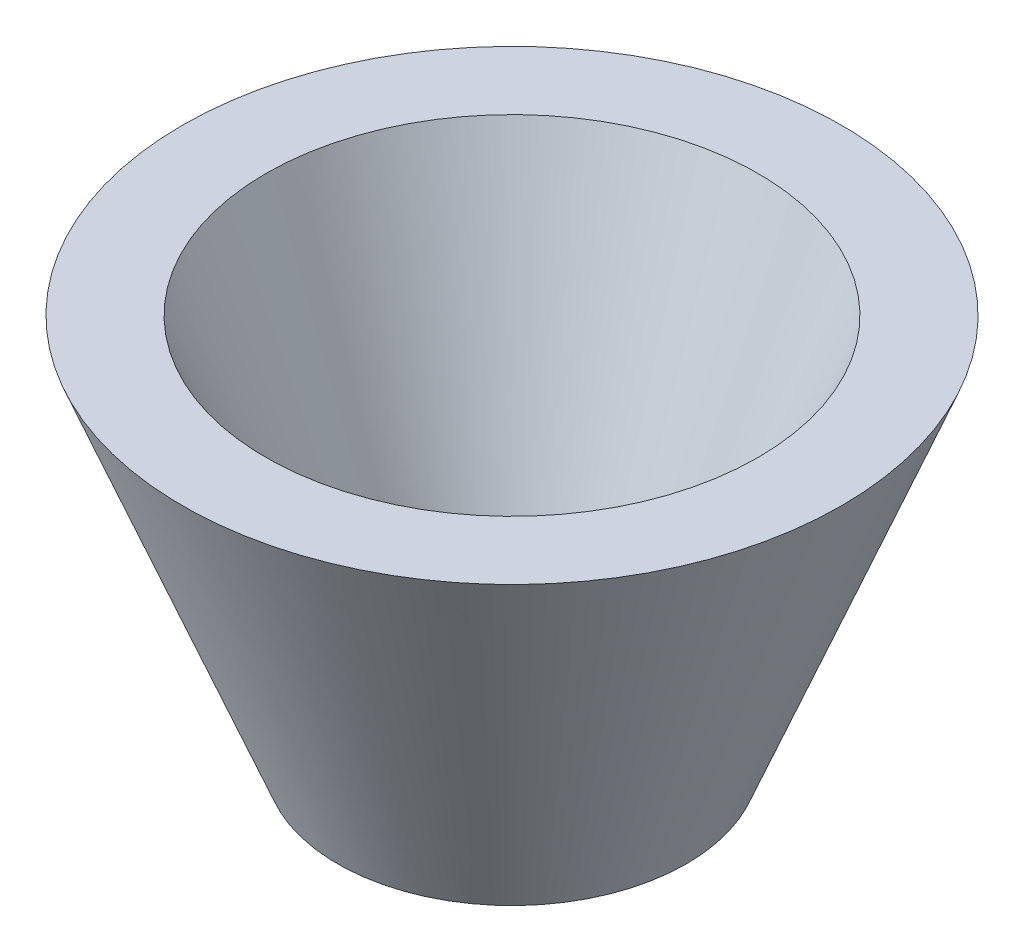
SolidWorks part; units mm, degrees
ref_plane "前视基准面" through (0, 0, 0) normal (0, 0, 1) x (1, 0, 0)
ref_plane "上视基准面" through (0, 0, 0) normal (0, 1, 0) x (1, 0, 0)
ref_plane "右视基准面" through (0, 0, 0) normal (1, 0, 0) x (0, 0, -1)
other "Configuration Table"
sketch "草图1" plane through (0, 0, 0) normal (0, 0, 1) x (1, 0, 0)
  line L0 (0, 0) -> (4.5, 0)
  line L1 (4.5, 0) -> (8.5, 10)
  line L2 (8.5, 10) -> (0, 10)
  line L3 (0, 10) -> (0, 0)
  point P3 (0, 0)
  dimension "D1" = 4.5
  dimension "D2" = 8.5
  dimension "D3" = 10
revolve "旋转1" add sketch "草图1" angle 360 about L3
shell "抽壳3" thickness 2
